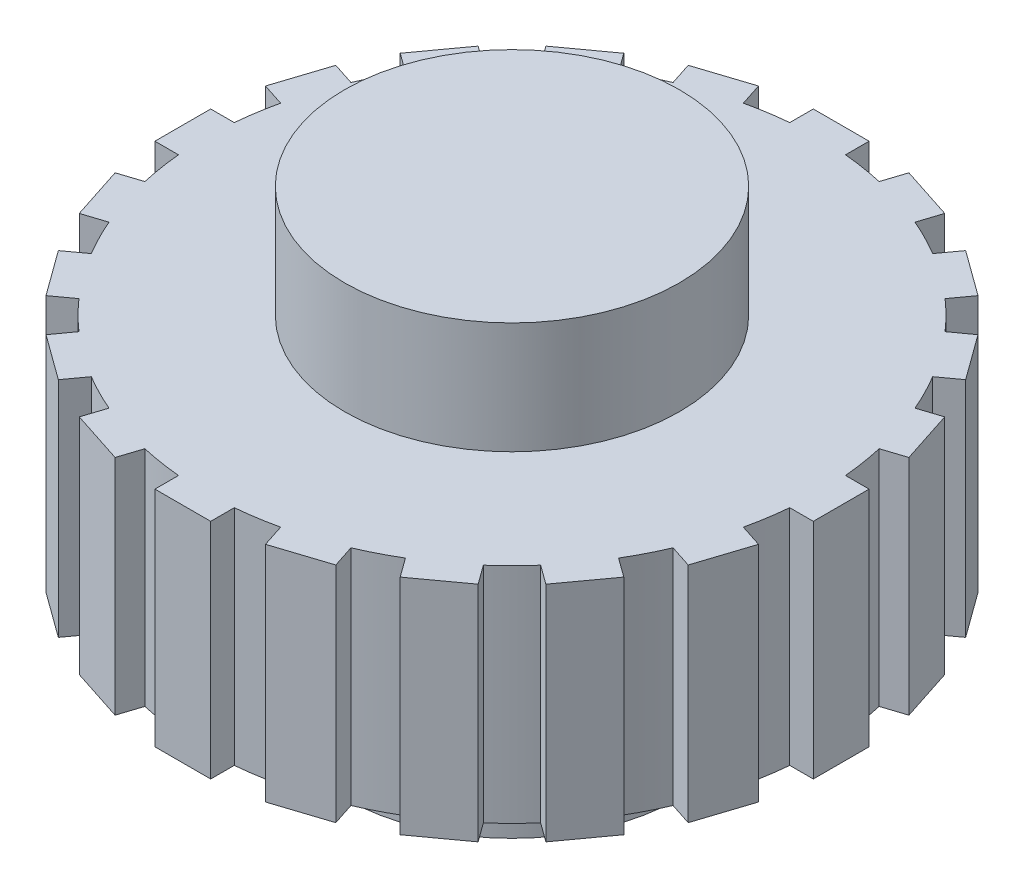
SolidWorks part; units mm, degrees
ref_plane "Plan de face" through (0, 0, 0) normal (0, 0, 1) x (1, 0, 0)
ref_plane "Plan de dessus" through (0, 0, 0) normal (0, 1, 0) x (1, 0, 0)
ref_plane "Plan de droite" through (0, 0, 0) normal (1, 0, 0) x (0, 0, -1)
sketch "Esquisse1" plane through (0, 0, 0) normal (0, 1, 0) x (1, 0, 0)
  circle A0 centre (0, 0) radius 15
  dimension "D1" = 30
extrude "Boss.-Extru.1" add sketch "Esquisse1" along normal blind 40
ref_plane "Plan1" through (0, 10, 0) normal (0, -1, 0) x (-1, 0, 0)
sketch "Esquisse2" plane through (0, 10, 0) normal (0, -1, 0) x (-1, 0, 0)
  circle A0 centre (0, 0) radius 27.5
  dimension "D1" = 55
extrude "Boss.-Extru.2" add sketch "Esquisse2" against normal blind 20
ref_plane "Plan2" through (0, 0, 22.5) normal (0, 0, 1) x (1, 0, 0)
sketch "Esquisse3" plane through (0, 0, 22.5) normal (0, 0, 1) x (1, 0, 0)
  line L0 (0, 10) -> (0, 30) construction
  line L1 (-16.5, 10) -> (16.5, 10) construction
  line L2 (27.5, 30) -> (-27.5, 30) construction
  line L4 (-2.5, 10) -> (2.5, 10)
  line L5 (-2.5, 10) -> (-2.5, 30)
  line L6 (-2.5, 30) -> (2.5, 30)
  line L7 (2.5, 10) -> (2.5, 30)
  line L8 (-2.5, 10) -> (2.5, 30) construction
  line L9 (-2.5, 30) -> (2.5, 10) construction
  point P6 (0, 20)
  dimension "D1" = 5
extrude "Boss.-Extru.3" add sketch "Esquisse3" along normal blind 7
pattern_circular "Répétition circulaire1" count 20 over 360 about axis through (0, 0, 0) along (0, 1, 0) of "Boss.-Extru.3"
